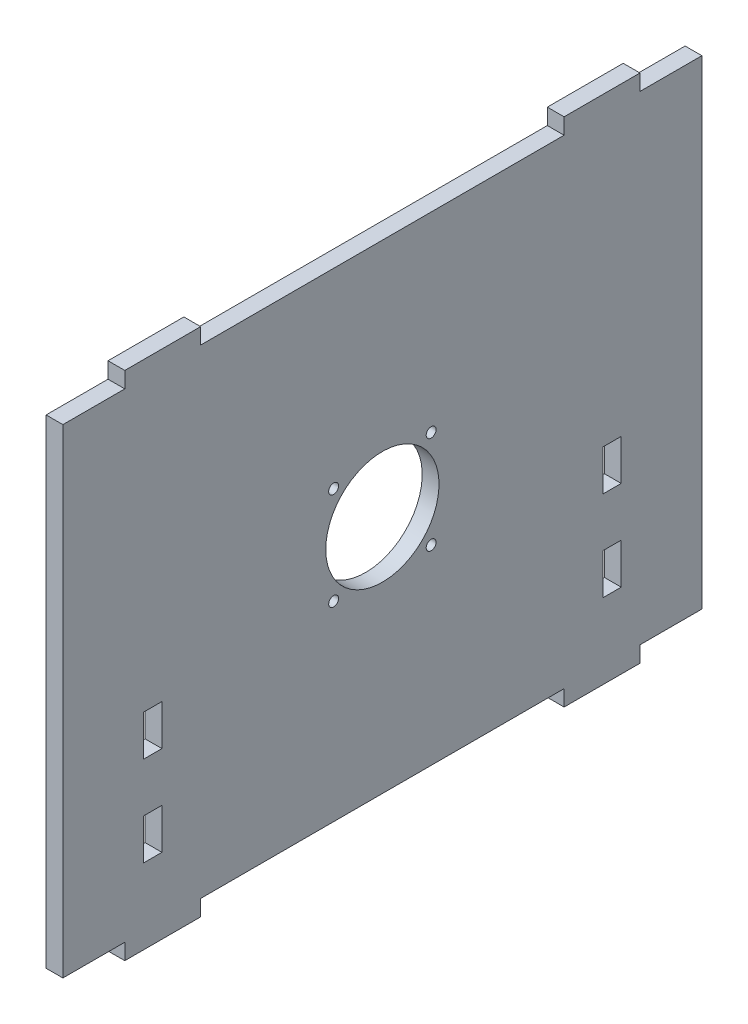
SolidWorks part; units mm, degrees
ref_plane "Front" through (0, 0, 0) normal (0, 0, 1) x (1, 0, 0)
ref_plane "Top" through (0, 0, 0) normal (0, 1, 0) x (1, 0, 0)
ref_plane "Right" through (0, 0, 0) normal (1, 0, 0) x (0, 0, -1)
sketch "Sketch1" plane through (0, 0, 0) normal (1, 0, 0) x (0, 0, -1)
  line L1 (-101.6, 0) -> (101.6, 0)
  line L2 (-101.6, 0) -> (-101.6, 152.4)
  line L3 (-101.6, 152.4) -> (101.6, 152.4)
  line L4 (101.6, 0) -> (101.6, 152.4)
  point P4 (0, 0)
  dimension "D1" = 203.2
  dimension "D2" = 152.4
extrude "Boss-Extrude2" add sketch "Sketch1" along normal blind 5.334
sketch "Sketch2" plane through (0, 0, 0) normal (-1, 0, 0) x (0, 0, 1)
  line L0 (101.6, 152.4) -> (101.6, 0) construction
  circle A0 centre (0, 76.2) radius 18
  circle A1 centre (-15.5, 91.7) radius 1.575
  circle A2 centre (15.5, 91.7) radius 1.575
  circle A3 centre (15.5, 60.7) radius 1.575
  circle A4 centre (-15.5, 60.7) radius 1.575
  point P14 (0, 76.2)
  point P15 (101.6, 76.2)
  dimension "D2" = 36
  dimension "D4" = 3.15
  dimension "D3" = 15.5
  dimension "D5" = 15.5
  dimension "D6" = 4
extrude "Cut-Extrude1" cut sketch "Sketch2" against normal through all
sketch "Sketch3" plane through (5.334, 0, 0) normal (1, 0, 0) x (0, 0, -1)
  line L0 (-101.6, 0) -> (101.6, 0) construction
  line L1 (57.785, 0) -> (81.915, 0)
  line L2 (57.785, 0) -> (57.785, -5.08)
  line L3 (57.785, -5.08) -> (81.915, -5.08)
  line L4 (81.915, 0) -> (81.915, -5.08)
  line L5 (101.6, 0) -> (101.6, 152.4) construction
  point P6 (69.85, 0)
  dimension "D1" = 5.08
  dimension "D2" = 24.13
  dimension "D3" = 31.75
extrude "Boss-Extrude3" add sketch "Sketch3" against normal through all
mirror "Mirror1" about plane through (0, 0, 0) normal (0, 0, 1) of "Boss-Extrude3"
sketch "Sketch4" plane through (5.334, 0, 0) normal (1, 0, 0) x (0, 0, -1)
  line L16 (81.915, 0) -> (101.6, 0) construction
  line L17 (70.104, 31.8135) -> (75.946, 31.8135)
  line L18 (70.104, 31.8135) -> (70.104, 18.8595)
  line L19 (70.104, 18.8595) -> (75.946, 18.8595)
  line L20 (75.946, 31.8135) -> (75.946, 18.8595)
  line L21 (70.104, 31.8135) -> (75.946, 18.8595) construction
  line L22 (70.104, 18.8595) -> (75.946, 31.8135) construction
  line L23 (70.104, 60.3885) -> (75.946, 60.3885)
  line L24 (70.104, 60.3885) -> (70.104, 47.4345)
  line L25 (70.104, 47.4345) -> (75.946, 47.4345)
  line L26 (75.946, 60.3885) -> (75.946, 47.4345)
  line L27 (70.104, 60.3885) -> (75.946, 47.4345) construction
  line L28 (70.104, 47.4345) -> (75.946, 60.3885) construction
  line L29 (101.6, 0) -> (101.6, 152.4) construction
  point P0 (73.025, 25.3365)
  point P5 (73.025, 53.9115)
  dimension "D1" = 28.575
  dimension "D2" = 5.842
  dimension "D3" = 12.954
  dimension "D4" = 25.3365
  dimension "D5" = 28.575
extrude "Cut-Extrude2" cut sketch "Sketch4" against normal through all
mirror "Mirror2" about plane through (0, 0, 0) normal (0, 0, 1) of "Cut-Extrude2"
ref_plane "Plane1" through (0, 76.2, 0) normal (0, -1, 0) x (-1, 0, 0)
mirror "Mirror3" about plane through (0, 76.2, 0) normal (0, -1, 0) of "Mirror1", "Boss-Extrude3"
